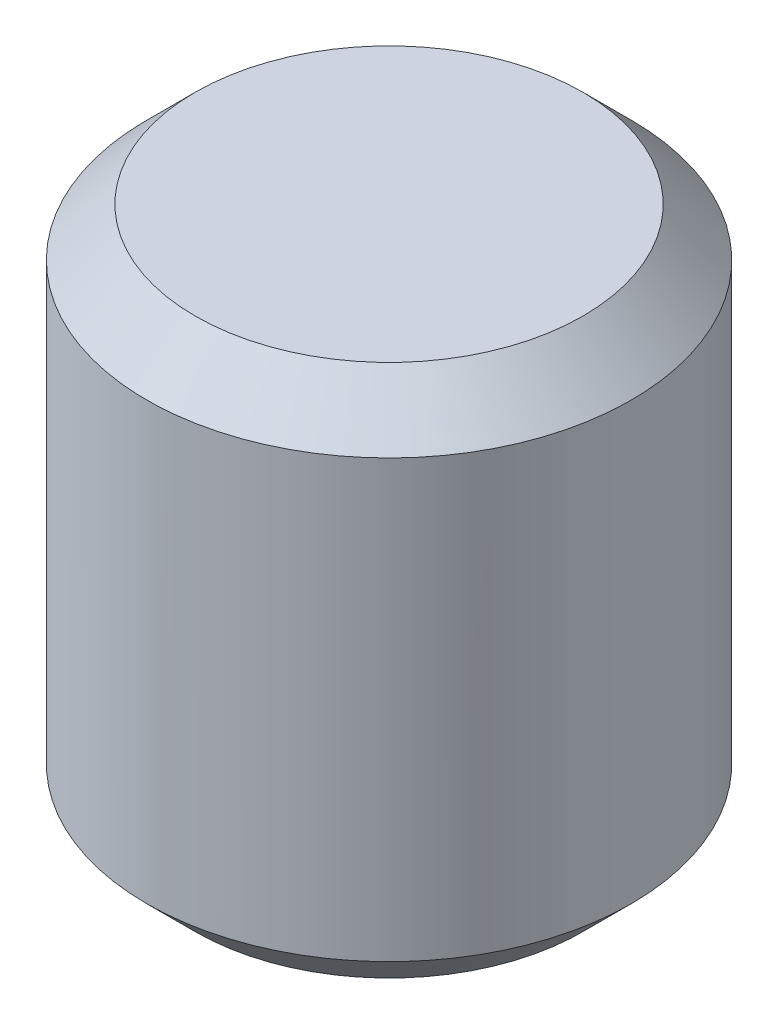
SolidWorks part; units mm, degrees
ref_plane "Front Plane" through (0, 0, 0) normal (0, 0, 1) x (1, 0, 0)
ref_plane "Top Plane" through (0, 0, 0) normal (0, 1, 0) x (1, 0, 0)
ref_plane "Right Plane" through (0, 0, 0) normal (1, 0, 0) x (0, 0, -1)
sketch "Sketch1" plane through (0, 0, 0) normal (0, 1, 0) x (1, 0, 0)
  circle A0 centre (0, 0) radius 1.75
  dimension "D1" = 3.5
extrude "Boss-Extrude1" add sketch "Sketch1" along normal blind 3.85
chamfer "Chamfer1" distance 0.35 angle 45 2 edges at (0, 3.85, 1.75) (0, 0, 1.75)
